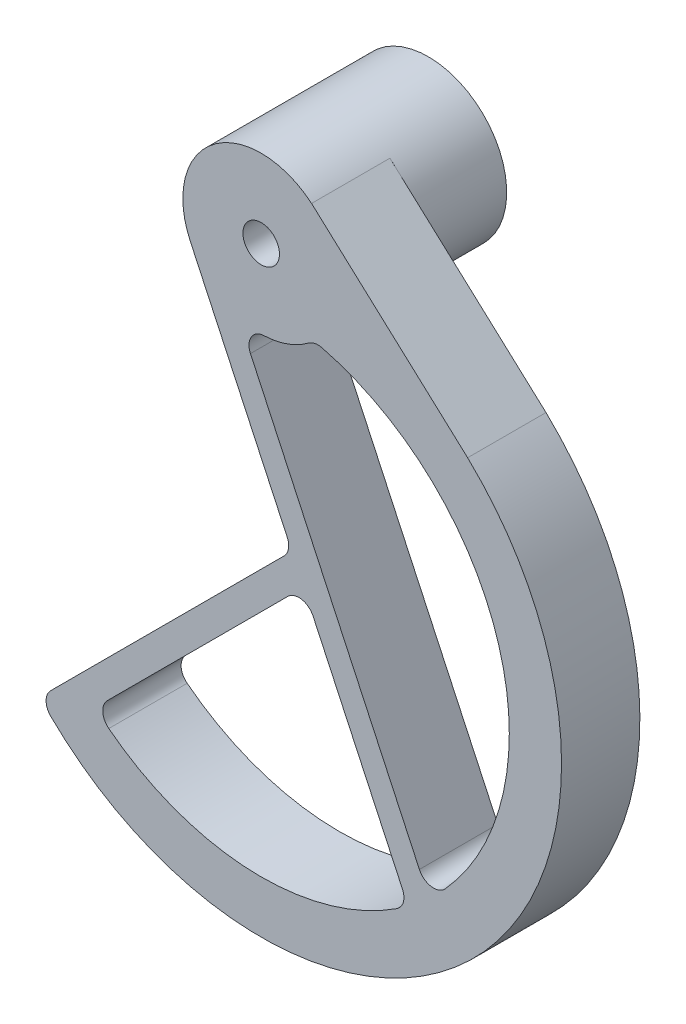
SolidWorks part; units mm, degrees
material "ABS"
ref_plane "正面" through (0, 0, 0) normal (0, 0, 1) x (1, 0, 0)
ref_plane "平面" through (0, 0, 0) normal (0, 1, 0) x (1, 0, 0)
ref_plane "右側面" through (0, 0, 0) normal (1, 0, 0) x (0, 0, -1)
sketch "ｽｹｯﾁ1" plane through (0, 0, 0) normal (0, 0, 1) x (1, 0, 0)
  line L1 (9.9336, 0.7043) -> (27.0462, -35.9938)
  line L2 (9.6418, 68.9907) -> (39.5241, 41.7624)
  line L4 (4.3888, 7.9244) -> (-40.3035, -36.7679)
  line L5 (5.0933, 1.5578) -> (-29.4572, -32.9928)
  line L6 (-13.5946, 51.1607) -> (4.9864, 11.3135)
  line L7 (30.2877, -31.1143) -> (-2.0547, 38.2444)
  arc A0 (-40.2839, -41.0299) -> (37.9168, 43.2269) centre (0, 0) ccw
  arc A1 (-29.1788, -37.4813) -> (25.9673, -39.7737) centre (0, 0) ccw
  arc A2 (0.5535, 42.5102) -> (9.0577, 45.5435) centre (0, 57.5) ccw
  arc A3 (35.2318, -31.8586) -> (11.602, 46.0613) centre (0, 0) ccw
  arc A4 (10.5469, 68.1659) -> (-13.5946, 51.1607) centre (0, 57.5) ccw
  arc A5 (-40.3035, -36.7679) -> (-40.2839, -41.0299) centre (-38.1821, -38.8893) ccw
  arc A6 (-29.4572, -32.9928) -> (-29.1788, -37.4813) centre (-27.3359, -35.1141) ccw
  arc A7 (27.0462, -35.9938) -> (25.9673, -39.7737) centre (24.3273, -37.2617) cw
  arc A8 (5.0933, 1.5578) -> (9.9336, 0.7043) centre (7.2147, -0.5635) cw
  arc A9 (35.2318, -31.8586) -> (30.2877, -31.1143) centre (33.0067, -29.8464) cw
  arc A10 (4.9864, 11.3135) -> (4.3888, 7.9244) centre (2.2675, 10.0457) cw
  arc A11 (-2.0547, 38.2444) -> (0.5535, 42.5102) centre (0.6642, 39.5123) cw
  arc A12 (11.602, 46.0613) -> (9.0577, 45.5435) centre (10.8692, 43.1522) ccw
  point P24 (8.1229, 4.5874)
  dimension "D1" = 3
  dimension "D2" = 3
  dimension "D3" = 3
  dimension "D4" = 3
  dimension "D5" = 3
  dimension "D6" = 3
  dimension "D7" = 3
  dimension "D8" = 3
extrude "ﾎﾞｽ - 押し出し1" add sketch "ｽｹｯﾁ1" along normal blind 15 contours L6 A10 L4 A5 A0 L2 A4 A12 A3 A9 L7 A11 A2 L5 A8 L1 A7 A1 A6
sketch "ｽｹｯﾁ6" plane through (0, 0, 15) normal (0, 0, 1) x (1, 0, 0)
  circle A0 centre (0, 57.5) radius 3.5
  dimension "D1" = 7
extrude "ｶｯﾄ - 押し出し2" cut sketch "ｽｹｯﾁ6" against normal blind 15
sketch "ｽｹｯﾁ11" plane through (0, 0, 0) normal (0, 0, -1) x (-1, 0, 0)
  circle A0 centre (0, 57.5) radius 15
  circle A1 centre (0, 57.5) radius 3.5
extrude "ﾎﾞｽ - 押し出し3" add sketch "ｽｹｯﾁ11" along normal blind 17
sketch "ｽｹｯﾁ12" plane through (0, 0, -17) normal (0, 0, -1) x (-1, 0, 0)
  circle A0 centre (0, 57.5) radius 10.1
extrude "ｶｯﾄ - 押し出し6" cut sketch "ｽｹｯﾁ12" against normal blind 2
sketch "ｽｹｯﾁ13" plane through (0, 0, -15) normal (0, 0, -1) x (-1, 0, 0)
  line L0 (0, 65.5) -> (-3.5, 65.5) construction
  line L1 (0, 57.5) -> (0, 65.5) construction
  line L2 (0, 65.5) -> (3.5, 65.5) construction
  circle A0 centre (-3.5, 65.5) radius 0.5
  circle A1 centre (0, 65.5) radius 0.5
  circle A2 centre (3.5, 65.5) radius 0.5
  circle A3 centre (8, 57.5) radius 0.5
  circle A4 centre (8, 61) radius 0.5
  circle A5 centre (8, 54) radius 0.5
  circle A6 centre (0, 49.5) radius 0.5
  circle A7 centre (3.5, 49.5) radius 0.5
  circle A8 centre (-3.5, 49.5) radius 0.5
  circle A9 centre (-8, 57.5) radius 0.5
  circle A10 centre (-8, 54) radius 0.5
  circle A11 centre (-8, 61) radius 0.5
  point P25 (0, 57.5)
extrude "ｶｯﾄ - 押し出し7" cut sketch "ｽｹｯﾁ13" against normal blind 3
